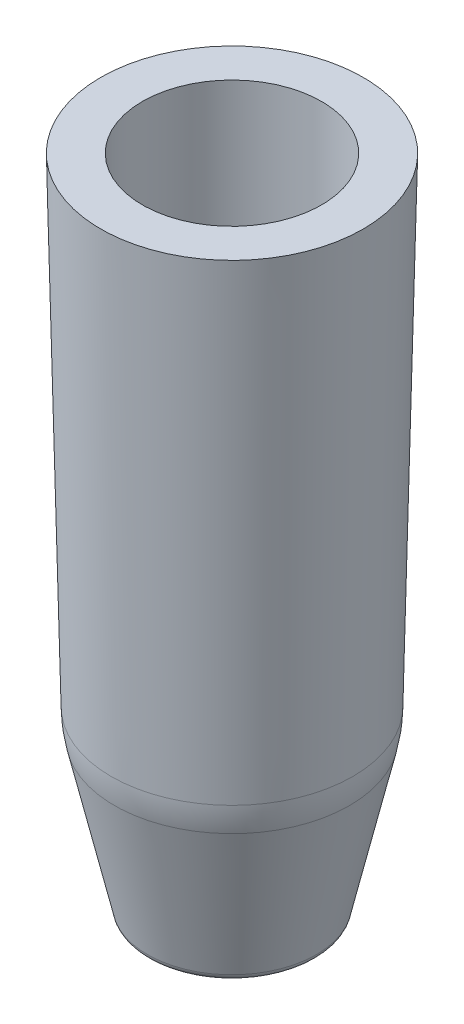
SolidWorks part; units mm, degrees
material "PA Тип 6"
ref_plane "Спереди" through (0, 0, 0) normal (0, 0, 1) x (1, 0, 0)
ref_plane "Сверху" through (0, 0, 0) normal (0, 1, 0) x (1, 0, 0)
ref_plane "Справа" through (0, 0, 0) normal (1, 0, 0) x (0, 0, -1)
sketch "Эскиз1" plane through (0, 0, 0) normal (0, 0, 1) x (1, 0, 0)
  line L0 (-2, 0) -> (-2.93, 0)
  line L1 (-2.93, 0) -> (-2.69, -11)
  line L2 (-2.69, -11) -> (-1.85, -14.7)
  line L3 (-1.85, -14.7) -> (-1, -14.7)
  line L4 (-1, -14.7) -> (-1.7, -8.1)
  line L5 (-1.7, -8.1) -> (-2, -7.8)
  line L6 (-2, -7.8) -> (-2, 0)
  line L7 (0, 0) -> (0, -14.7) construction
  dimension "D1" = 5.86
  dimension "D2" = 5.38
  dimension "D3" = 11
  dimension "D4" = 14.7
  dimension "D5" = 3.7
  dimension "D6" = 2
  dimension "D7" = 4
  dimension "D8" = 7.8
  dimension "D9" = 45
  dimension "D10" = 0.3
revolve "Повернуть1" add sketch "Эскиз1" angle 360 about L7
fillet "Скругление1" radius 0.2 1 edges at (-1.85, -14.7, 0)
fillet "Скругление2" radius 3 1 edges at (-2.69, -11, 0)
